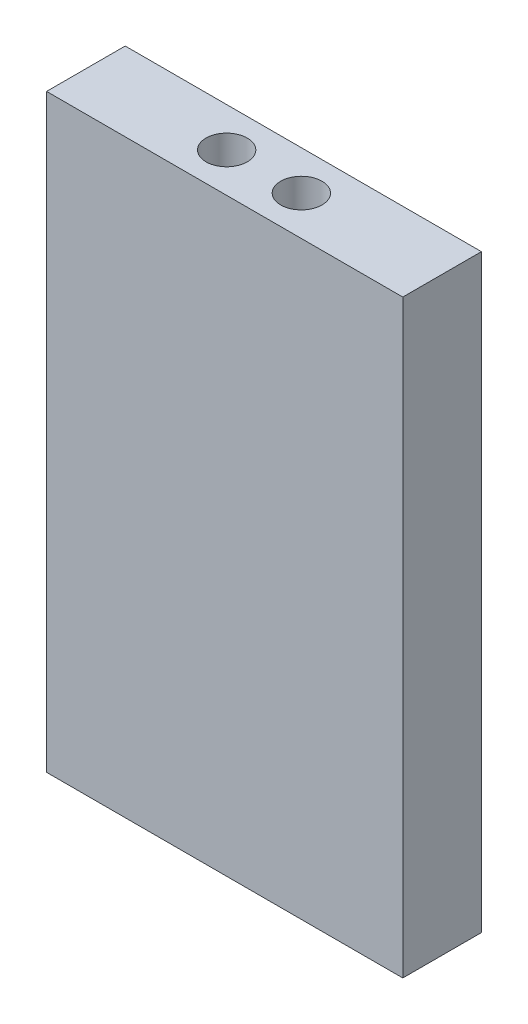
SolidWorks part; units mm, degrees
ref_plane "Front Plane" through (0, 0, 0) normal (0, 0, 1) x (1, 0, 0)
ref_plane "Top Plane" through (0, 0, 0) normal (0, 1, 0) x (1, 0, 0)
ref_plane "Right Plane" through (0, 0, 0) normal (1, 0, 0) x (0, 0, -1)
sketch "Sketch1" plane through (0, 0, 0) normal (0, 0, 1) x (1, 0, 0)
  line L1 (-99.435, 92.0904) -> (0.565, 92.0904)
  line L2 (-99.435, 92.0904) -> (-99.435, -57.9096)
  line L3 (-99.435, -57.9096) -> (0.565, -57.9096)
  line L4 (0.565, 92.0904) -> (0.565, -57.9096)
  dimension "D1" = 150
  dimension "D2" = 100
extrude "Boss-Extrude1" add sketch "Sketch1" along normal blind 20
sketch "Sketch2" plane through (0, 92.0904, 0) normal (0, 1, 0) x (1, 0, 0)
  circle A1 centre (-58.935, -10) radius 5.25
  circle A2 centre (-39.935, -10) radius 5.25
extrude "Cut-Extrude1" cut sketch "Sketch2" against normal blind 26
sketch "Sketch3" plane through (0, 0, 20) normal (0, 0, 1) x (1, 0, 0)
  line L0 (-99.435, -57.9096) -> (0.565, -57.9096) construction
  line L1 (-99.435, 92.0904) -> (-94.735, 92.0904)
  line L2 (-99.435, 92.0904) -> (-99.435, -57.9096)
  line L3 (-99.435, -57.9096) -> (-94.735, -57.9096)
  line L4 (-94.735, 92.0904) -> (-94.735, -57.9096)
  line L6 (0.565, 92.0904) -> (-4.135, 92.0904)
  line L7 (0.565, 92.0904) -> (0.565, -57.9096)
  line L8 (0.565, -57.9096) -> (-4.135, -57.9096)
  line L9 (-4.135, 92.0904) -> (-4.135, -57.9096)
  dimension "D1" = 4.7
  dimension "D2" = 4.7
extrude "Cut-Extrude2" cut sketch "Sketch3" against normal up to surface (20 mm away) up to face at (-49.435, 17.0904, 0)
